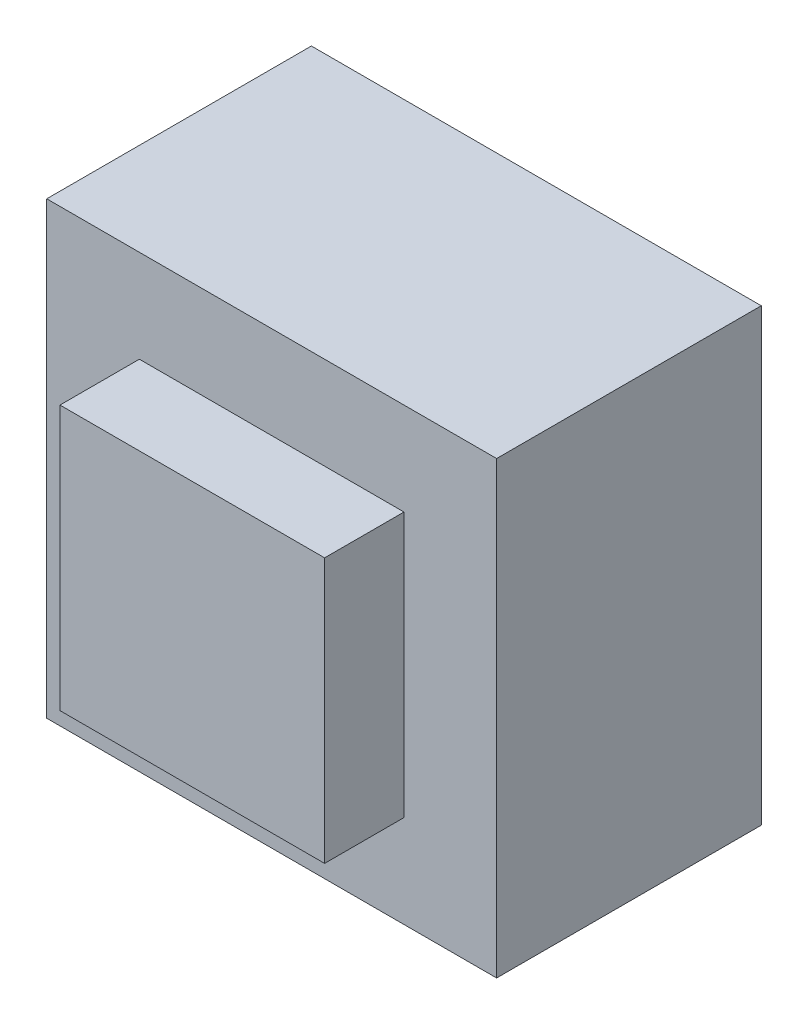
SolidWorks part; units mm, degrees
material "C (Графит)"
ref_plane "Спереди" through (0, 0, 0) normal (0, 0, 1) x (1, 0, 0)
ref_plane "Сверху" through (0, 0, 0) normal (0, 1, 0) x (1, 0, 0)
ref_plane "Справа" through (0, 0, 0) normal (1, 0, 0) x (0, 0, -1)
sketch "Эскиз5" plane through (0, 0, 0) normal (0, 0, 1) x (1, 0, 0)
  line L5 (0, 0) -> (0, 1.7)
  line L10 (0, 0) -> (1.7, 0)
  line L11 (0, 1.7) -> (1.7, 1.7)
  line L12 (1.7, 0) -> (1.7, 1.7)
  dimension "D1" = 1.7
  dimension "D2" = 1.7
extrude "Бобышка-Вытянуть3" add sketch "Эскиз5" along normal blind 1
sketch "Эскиз17" plane through (0, 0, 1) normal (0, 0, 1) x (1, 0, 0)
  line L0 (0.35, 1.35) -> (0.35, 0.35)
  line L1 (0.35, 1.35) -> (1.35, 1.35)
  line L2 (0.35, 0.35) -> (1.35, 0.35)
  line L3 (1.35, 1.35) -> (1.35, 0.35)
  line L4 (1.7, 1.7) -> (0, 1.7) construction
  line L5 (0, 1.7) -> (0, 0) construction
  dimension "D1" = 1
  dimension "D2" = 1
  dimension "D3" = 0.35
  dimension "D4" = 0.35
extrude "Бобышка-Вытянуть4" add sketch "Эскиз17" along normal blind 0.3
